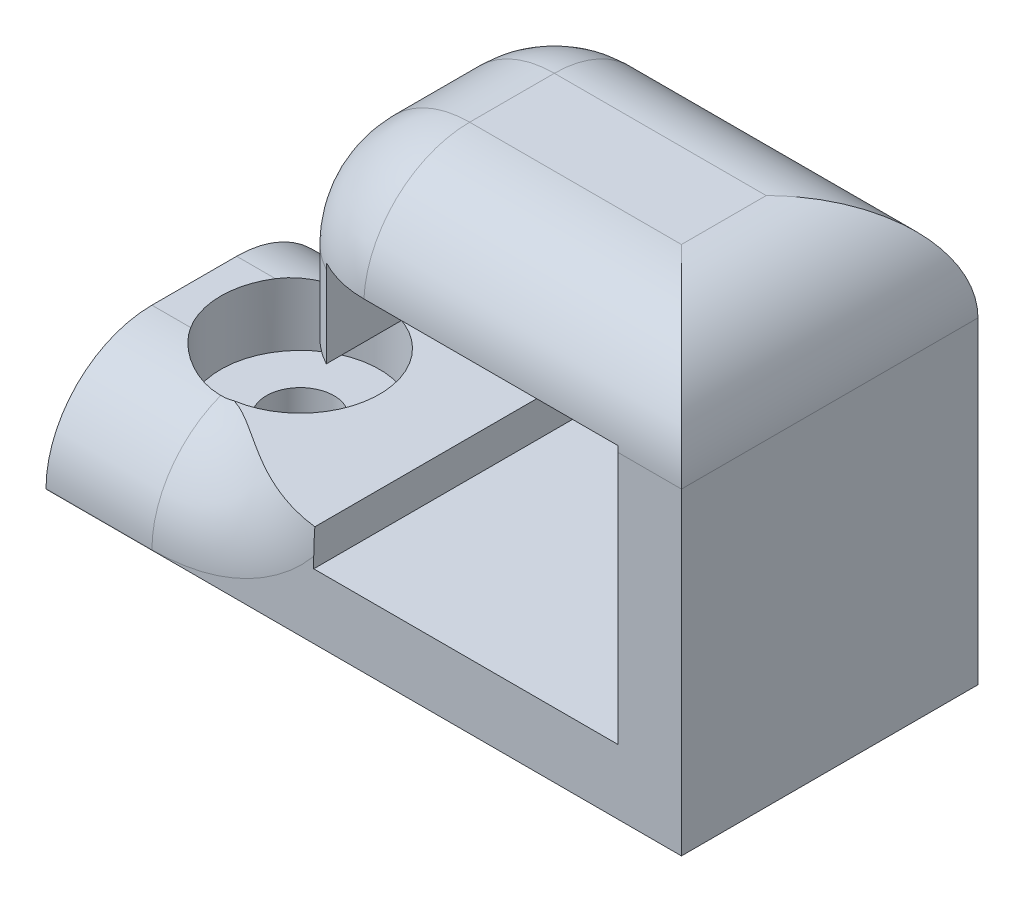
SolidWorks part; units mm, degrees
ref_plane "Front Plane" through (0, 0, 0) normal (0, 0, 1) x (1, 0, 0)
ref_plane "Top Plane" through (0, 0, 0) normal (0, 1, 0) x (1, 0, 0)
ref_plane "Right Plane" through (0, 0, 0) normal (1, 0, 0) x (0, 0, -1)
sketch "Sketch1" plane through (0, 0, 0) normal (0, 1, 0) x (1, 0, 0)
  line L1 (-9.87, 7.8499) -> (20.13, 7.8499)
  line L2 (-9.87, 7.8499) -> (-9.87, -6.1501)
  line L3 (-9.87, -6.1501) -> (20.13, -6.1501)
  line L4 (20.13, 7.8499) -> (20.13, -6.1501)
  dimension "D1" = 14
  dimension "D2" = 30
extrude "Boss-Extrude1" add sketch "Sketch1" along normal blind 20
sketch "Sketch2" plane through (0, 0, 6.1501) normal (0, 0, 1) x (1, 0, 0)
  line L1 (-9.87, 20) -> (0.13, 20)
  line L2 (-9.87, 20) -> (-9.87, 5.0189)
  line L3 (-9.87, 5.0189) -> (0.13, 5.0189)
  line L4 (0.13, 20) -> (0.13, 5.0189)
  dimension "D1" = 10
extrude "Cut-Extrude1" cut sketch "Sketch2" against normal blind 20
fillet "Fillet1" radius 5 9 edges at (-4.87, 5.0189, -7.8499) (-4.87, 5.0189, 6.1501) (10.13, 20, -7.8499) (20.13, 20, -0.8499) (10.13, 20, 6.1501) (0.13, 12.5095, -7.8499) (0.13, 20, -0.8499) (0.13, 12.5095, 6.1501) (0.13, 5.0189, -0.8499)
sketch "Sketch3" plane through (0, 0, -7.8499) normal (0, 0, -1) x (-1, 0, 0)
  line L1 (-12.696, 11.1415) -> (4.243, 11.1415)
  line L2 (-12.696, 11.1415) -> (-12.696, 7.8553)
  line L3 (-12.696, 7.8553) -> (4.243, 7.8553)
  line L4 (4.243, 11.1415) -> (4.243, 7.8553)
extrude "Cut-Extrude2" cut sketch "Sketch3" against normal blind 20
sketch "Sketch4" plane through (0, 0, -7.8499) normal (0, 0, -1) x (-1, 0, 0)
  line L0 (-5.13, 15) -> (-20.13, 15) construction
  line L1 (-12.63, 15) -> (-5.13, 15)
  line L2 (-12.63, 15) -> (-12.63, 4.7525)
  line L3 (-12.63, 4.7525) -> (-5.13, 4.7525)
  line L4 (-5.13, 15) -> (-5.13, 4.7525)
extrude "Cut-Extrude3" cut sketch "Sketch4" against normal blind 20
sketch "Sketch5" plane through (0, 5.0189, 0) normal (0, 1, 0) x (1, 0, 0)
  line L0 (-4.87, -1.1501) -> (-4.87, 2.8499) construction
  circle A0 centre (-4.87, 0.8499) radius 1.6
  dimension "D1" = 3.2
extrude "Cut-Extrude5" cut sketch "Sketch5" against normal blind 20 and the other way blind 20
sketch "Sketch6" plane through (0, 5.0189, 0) normal (0, 1, 0) x (1, 0, 0)
  circle A0 centre (-4.87, 0.8499) radius 3.75
  dimension "D1" = 7.5
extrude "Cut-Extrude6" cut sketch "Sketch6" against normal blind 3 and the other way blind 5
sketch "Sketch8" plane through (0, 0, -7.8499) normal (0, 0, -1) x (-1, 0, 0)
  line L1 (-5.13, 4.7525) -> (5.3372, 4.7525)
  line L2 (-5.13, 4.7525) -> (-5.13, 10.1789)
  line L3 (-5.13, 10.1789) -> (5.3372, 10.1789)
  line L4 (5.3372, 4.7525) -> (5.3372, 10.1789)
extrude "Cut-Extrude8" cut sketch "Sketch8" against normal blind 20
sketch "Sketch9" plane through (0, 0, -7.8499) normal (0, 0, -1) x (-1, 0, 0)
  line L0 (-12.63, 15) -> (-20.13, 15) construction
  line L1 (-12.63, 4.7525) -> (-14.801, 4.7525)
  line L2 (-12.63, 4.7525) -> (-12.63, 15)
  line L3 (-12.63, 15) -> (-14.801, 15)
  line L4 (-14.801, 4.7525) -> (-14.801, 15)
extrude "Cut-Extrude9" cut sketch "Sketch9" against normal blind 20
sketch "Sketch10" plane through (0, 0, -7.8499) normal (0, 0, -1) x (-1, 0, 0)
  line L1 (-17.1271, 3.0596) -> (-2.7699, 3.0596)
  line L2 (-17.1271, 3.0596) -> (-17.1271, 15.2713)
  line L3 (-17.1271, 15.2713) -> (-2.7699, 15.2713)
  line L4 (-2.7699, 3.0596) -> (-2.7699, 15.2713)
extrude "Cut-Extrude12" cut sketch "Sketch10" against normal blind 20
